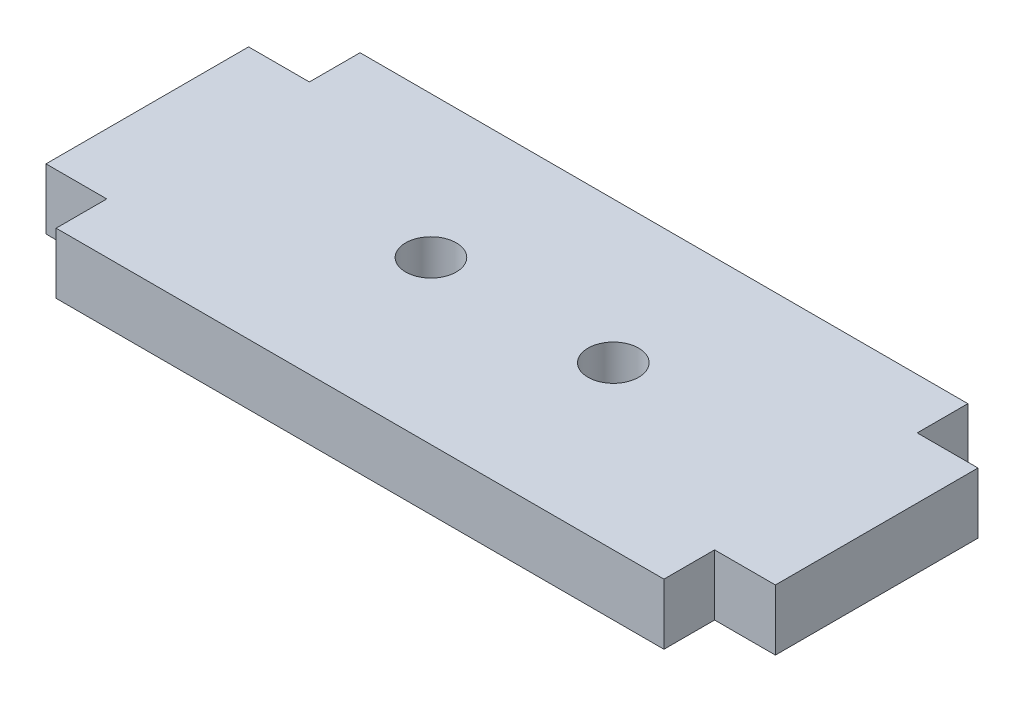
SolidWorks part; units mm, degrees
material "ABS"
ref_plane "Front Plane" through (0, 0, 0) normal (0, 0, 1) x (1, 0, 0)
ref_plane "Top Plane" through (0, 0, 0) normal (0, 1, 0) x (1, 0, 0)
ref_plane "Right Plane" through (0, 0, 0) normal (1, 0, 0) x (0, 0, -1)
sketch "Sketch1" plane through (0, 0, 0) normal (0, 1, 0) x (1, 0, 0)
  line L0 (0, 12.5) -> (0, 15)
  line L1 (0, 0) -> (30, 0)
  line L2 (0, 0) -> (0, 2.5)
  line L3 (0, 15) -> (30, 15)
  line L4 (30, 0) -> (30, 2.5)
  line L5 (30, 12.5) -> (33, 12.5)
  line L7 (30, 2.5) -> (33, 2.5)
  line L8 (33, 12.5) -> (33, 2.5)
  line L9 (0, 12.5) -> (-3, 12.5)
  line L11 (0, 2.5) -> (-3, 2.5)
  line L12 (-3, 12.5) -> (-3, 2.5)
  line L13 (30, 12.5) -> (30, 15)
  circle A0 centre (10.5, 8) radius 1.25
  circle A1 centre (19.5, 8) radius 1.25
  point P17 (0, 0)
  point P18 (0, 0)
  dimension "D9" = 2.5
  dimension "D10" = 2.5
  dimension "D1" = 30
  dimension "D2" = 15
  dimension "D3" = 10
  dimension "D4" = 3
  dimension "D5" = 10
  dimension "D6" = 3
  dimension "D7" = 2.5
  dimension "D8" = 2.5
  dimension "D11" = 9
  dimension "D12" = 8
  dimension "D13" = 10.5
extrude "Boss-Extrude1" add sketch "Sketch1" along normal blind 3
